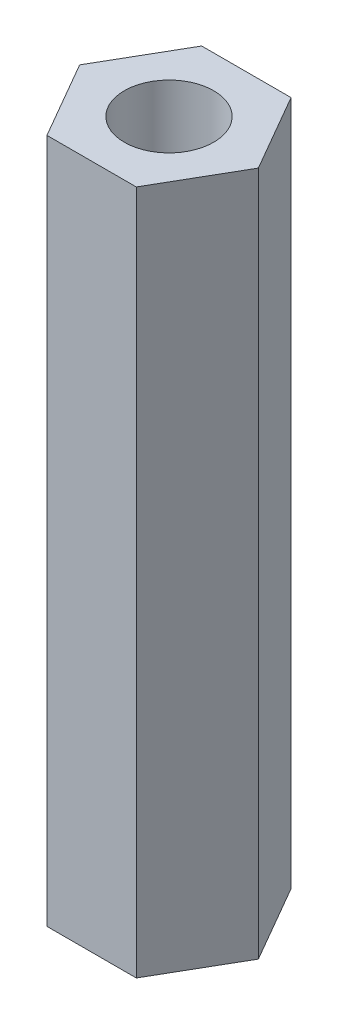
SolidWorks part; units mm, degrees
ref_plane "Plan de face" through (0, 0, 0) normal (0, 0, 1) x (1, 0, 0)
ref_plane "Plan de dessus" through (0, 0, 0) normal (0, 1, 0) x (1, 0, 0)
ref_plane "Plan de droite" through (0, 0, 0) normal (1, 0, 0) x (0, 0, -1)
sketch "Esquisse1" plane through (0, 0, 0) normal (0, 1, 0) x (1, 0, 0)
  line L0 (0, 0) -> (3, 0) construction
  line L1 (3, 0) -> (1.5, 2.5981)
  line L2 (1.5, 2.5981) -> (-1.5, 2.5981)
  line L3 (-1.5, 2.5981) -> (-3, 0)
  line L4 (-3, 0) -> (-1.5, -2.5981)
  line L5 (-1.5, -2.5981) -> (1.5, -2.5981)
  line L6 (1.5, -2.5981) -> (3, 0)
  circle A0 centre (0, 0) radius 2.5981 construction
  dimension "D1" = 3
extrude "Boss.-Extru.1" add sketch "Esquisse1" along normal blind 23
sketch "Sketch1" plane through (0, 23, 0) normal (0, 1, 0) x (1, 0, 0)
  circle A0 centre (0, 0) radius 1.5
  dimension "D1" = 3
extrude "Cut-Extrude1" cut sketch "Sketch1" against normal through all
